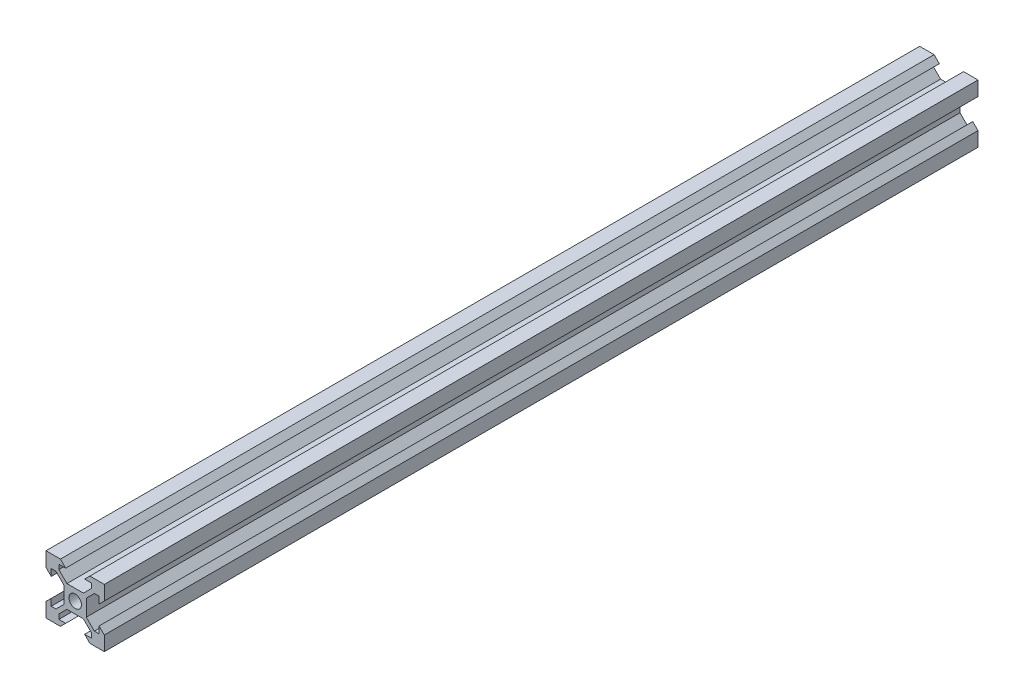
SolidWorks part; units mm, degrees
ref_plane "Alzado" through (0, 0, 0) normal (0, 0, 1) x (1, 0, 0)
ref_plane "Planta" through (0, 0, 0) normal (0, 1, 0) x (1, 0, 0)
ref_plane "Vista lateral" through (0, 0, 0) normal (1, 0, 0) x (0, 0, -1)
sketch "Croquis1" plane through (0, 0, 0) normal (0, 0, 1) x (1, 0, 0)
  line L0 (0, 0) -> (0, -20) construction
  line L2 (0, 0) -> (0, -0.5674)
  line L5 (6.175, -7.1649) -> (6.175, -12.8351)
  line L6 (7.1649, -13.825) -> (12.8351, -13.825)
  line L7 (13.825, -7.1649) -> (13.825, -12.8351)
  line L8 (7.1649, -6.175) -> (12.8351, -6.175)
  line L9 (6.175, -13.825) -> (13.825, -13.825) construction
  line L10 (13.825, -6.175) -> (13.825, -13.825) construction
  line L12 (10, -10) -> (32.1172, -10) construction
  line L13 (13.25, -18.2) -> (15.05, -20)
  line L14 (20, -20) -> (15.6, -20)
  line L15 (20, -20) -> (20, -15.6)
  line L16 (18.2, -15.6) -> (16.5899, -15.6)
  line L32 (15.6, -18.2) -> (15.6, -16.5899)
  line L33 (10, -10) -> (10, -23.2493) construction
  line L34 (4.4, -18.2) -> (4.4, -16.5899)
  line L35 (7.1649, -13.825) -> (4.4, -16.5899)
  line L36 (15.6, -18.2) -> (13.25, -18.2)
  line L38 (15.6, -20) -> (15.05, -20)
  line L40 (15.05, -20) -> (20, -20)
  line L41 (0, -20) -> (20, -20) construction
  line L42 (6.175, -12.8351) -> (3.4101, -15.6)
  line L43 (18.2, -13.25) -> (20, -15.05)
  line L44 (20, -20) -> (18.2, -20)
  line L45 (20, -20) -> (20, -15.05)
  line L48 (20, -15.05) -> (20, -20)
  line L49 (20, 0) -> (20, -20) construction
  line L50 (18.2, -15.6) -> (18.2, -13.25)
  line L51 (12.8351, -13.825) -> (15.6, -16.5899)
  line L52 (13.825, -12.8351) -> (16.5899, -15.6)
  line L53 (1.8, -15.6) -> (3.4101, -15.6)
  line L54 (1.8, -15.6) -> (1.8, -13.25)
  line L55 (1.8, -13.25) -> (0, -15.05)
  line L56 (0, 0) -> (20, 0) construction
  line L57 (0, -20) -> (0, -15.6)
  line L58 (0, -15.6) -> (0, -15.05)
  line L59 (0, -20) -> (4.4, -20)
  line L60 (0, -20) -> (4.95, -20)
  line L61 (6.75, -18.2) -> (4.95, -20)
  line L62 (4.4, -18.2) -> (6.75, -18.2)
  line L63 (1.8, -4.4) -> (3.4101, -4.4)
  line L64 (6.175, -7.1649) -> (3.4101, -4.4)
  line L65 (7.1649, -6.175) -> (4.4, -3.4101)
  line L66 (4.4, -1.8) -> (4.4, -3.4101)
  line L67 (4.4, -1.8) -> (6.75, -1.8)
  line L68 (6.75, -1.8) -> (4.95, 0)
  line L69 (0, 0) -> (4.4, 0)
  line L70 (4.4, 0) -> (4.95, 0)
  line L71 (0, 0) -> (0, -4.4)
  line L72 (0, 0) -> (0, -4.95)
  line L73 (1.8, -6.75) -> (0, -4.95)
  line L74 (1.8, -4.4) -> (1.8, -6.75)
  line L75 (15.6, -1.8) -> (15.6, -3.4101)
  line L76 (12.8351, -6.175) -> (15.6, -3.4101)
  line L77 (13.825, -7.1649) -> (16.5899, -4.4)
  line L78 (18.2, -4.4) -> (16.5899, -4.4)
  line L79 (18.2, -4.4) -> (18.2, -6.75)
  line L80 (18.2, -6.75) -> (20, -4.95)
  line L81 (20, 0) -> (20, -4.4)
  line L82 (20, -4.4) -> (20, -4.95)
  line L83 (20, 0) -> (15.6, 0)
  line L84 (20, 0) -> (15.05, 0)
  line L85 (13.25, -1.8) -> (15.05, 0)
  line L86 (15.6, -1.8) -> (13.25, -1.8)
  line L87 (6.175, -6.175) -> (13.825, -6.175) construction
  line L88 (6.175, -6.175) -> (6.175, -13.825) construction
  circle A0 centre (10, -10) radius 2.15
  point P69 (10, -10)
  dimension "D3" = 4.3
  dimension "D2" = 4
  dimension "D11" = 4.4
  dimension "D15" = 4.4
  dimension "D16" = 6.75
extrude "BoschBase" add sketch "Croquis1" along normal blind 299.71 contours L86 L75 L76 L8 L65 L66 L67 L68 L70 L69 L2 L71 L72 L73 L74 L63 L64 L5 L42 L53 L54 L55 L58 L57 L59 L60 L61 L62 L34 L35 L6 L51 L32 L36 L13 L38 L40 L14 L15 L45 L43 L50 L16 L52 L7 L77 L78 L79 L80 L82 L81
